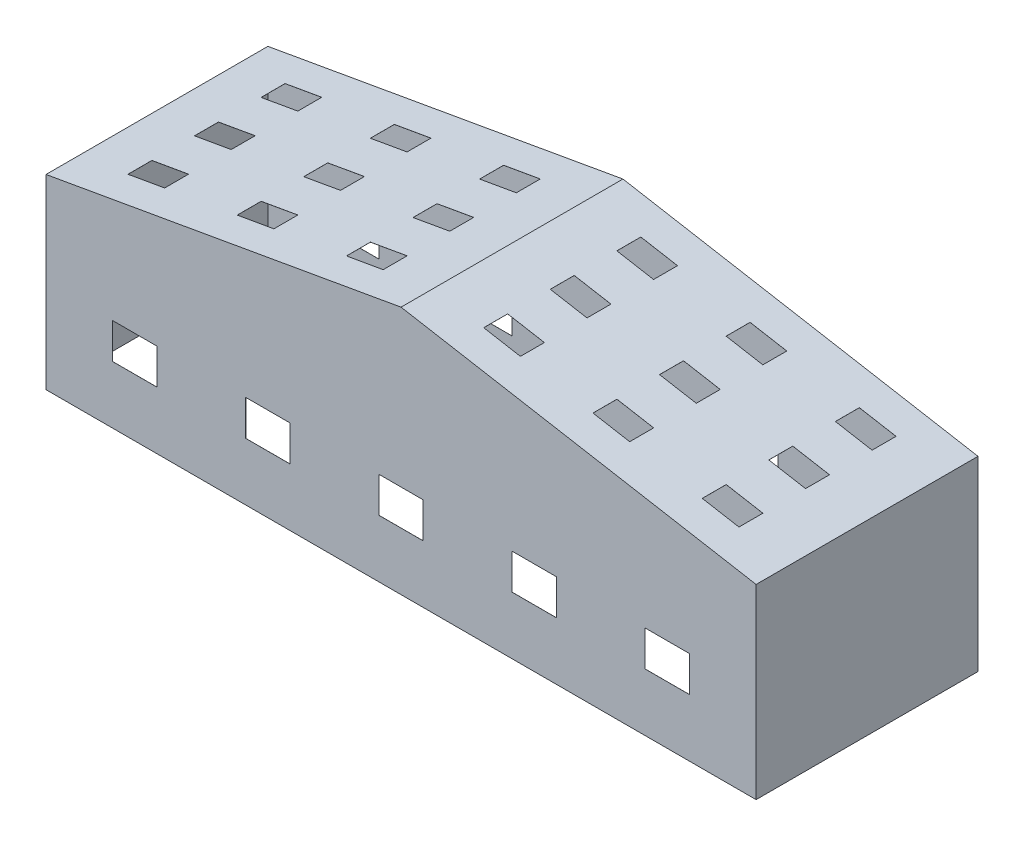
SolidWorks part; units mm, degrees
ref_plane "Front Plane" through (0, 0, 0) normal (0, 0, 1) x (1, 0, 0)
ref_plane "Top Plane" through (0, 0, 0) normal (0, 1, 0) x (1, 0, 0)
ref_plane "Right Plane" through (0, 0, 0) normal (1, 0, 0) x (0, 0, -1)
sketch "Sketch2" plane through (0, 0, 0) normal (0, 1, 0) x (1, 0, 0)
  line L1 (-8000, -2500) -> (8000, -2500)
  line L2 (-8000, -2500) -> (-8000, 2500)
  line L3 (-8000, 2500) -> (8000, 2500)
  line L4 (8000, -2500) -> (8000, 2500)
  line L5 (-8000, -2500) -> (8000, 2500) construction
  line L6 (-8000, 2500) -> (8000, -2500) construction
  line L7 (-8500, -3000) -> (8500, -3000)
  line L8 (-8500, -3000) -> (-8500, 3000)
  line L9 (-8500, 3000) -> (8500, 3000)
  line L10 (8500, -3000) -> (8500, 3000)
  line L11 (-8500, -3000) -> (8500, 3000) construction
  line L12 (-8500, 3000) -> (8500, -3000) construction
  point P0 (0, 0)
  point P6 (0, 0)
  dimension "D1" = 16000
  dimension "D2" = 5000
  dimension "D3" = 500
  dimension "D4" = 500
extrude "Boss-Extrude1" add sketch "Sketch2" along normal blind 4200 contours L1 L4 L3 L2
sketch "Sketch3" plane through (0, 0, 0) normal (0, 0, 1) x (1, 0, 0)
  line L0 (-8000, 4200) -> (0, 5610.6158)
  line L1 (0, 5610.6158) -> (8000, 4200)
  line L3 (-8000, 4200) -> (8000, 4200)
  dimension "D1" = 10
extrude "Boss-Extrude2" add sketch "Sketch3" along normal mid plane 5000
shell "Shell1" thickness 1
sketch "Sketch4" plane through (0, 0, 2500) normal (0, 0, 1) x (1, 0, 0)
  line L0 (-8500, 0) -> (8500, 0) construction
  line L1 (-500, 2100) -> (500, 2100)
  line L2 (-500, 2100) -> (-500, 1300)
  line L3 (-500, 1300) -> (500, 1300)
  line L4 (500, 2100) -> (500, 1300)
  line L5 (-500, 2100) -> (500, 1300) construction
  line L6 (-500, 1300) -> (500, 2100) construction
  point P0 (0, 1700)
  dimension "D1" = 1000
  dimension "D2" = 800
  dimension "D3" = 1300
extrude "Cut-Extrude1" cut sketch "Sketch4" against normal up to surface (4999 mm away)
pattern_linear "LPattern1" count 3 spacing 3000 along (-1, 0, 0) of "Cut-Extrude1"
mirror "Mirror1" about plane through (0, 0, 0) normal (1, 0, 0) of "LPattern1"
mirror "Mirror4" about plane through (0, 0, 0) normal (0, 0, 1) of "Mirror1", "LPattern1", "Cut-Extrude1"
sketch "Sketch5" plane through (959.4718, 5441.4351, 0) normal (0.1736, 0.9848, 0) x (0.9848, -0.1736, 0)
  line L0 (7149.1397, 2500) -> (-974.2732, 2500) construction
  line L1 (175.7268, 1770) -> (1015.7268, 1770)
  line L2 (175.7268, 1770) -> (175.7268, 1230)
  line L3 (175.7268, 1230) -> (1015.7268, 1230)
  line L4 (1015.7268, 1770) -> (1015.7268, 1230)
  line L7 (-974.2732, -2500) -> (-974.2732, 2500) construction
  dimension "D1" = 840
  dimension "D2" = 540
  dimension "D3" = 730
  dimension "D4" = 1150
extrude "Cut-Extrude2" cut sketch "Sketch5" against normal blind 1
pattern_linear "LPattern2" count 3 spacing 1500 along (0, 0, 1) count 3 spacing 2500 along (0.9848, -0.1736, 0) of "Cut-Extrude2"
mirror "Mirror9" about plane through (0, 0, 0) normal (1, 0, 0) of "LPattern2", "Cut-Extrude2"
